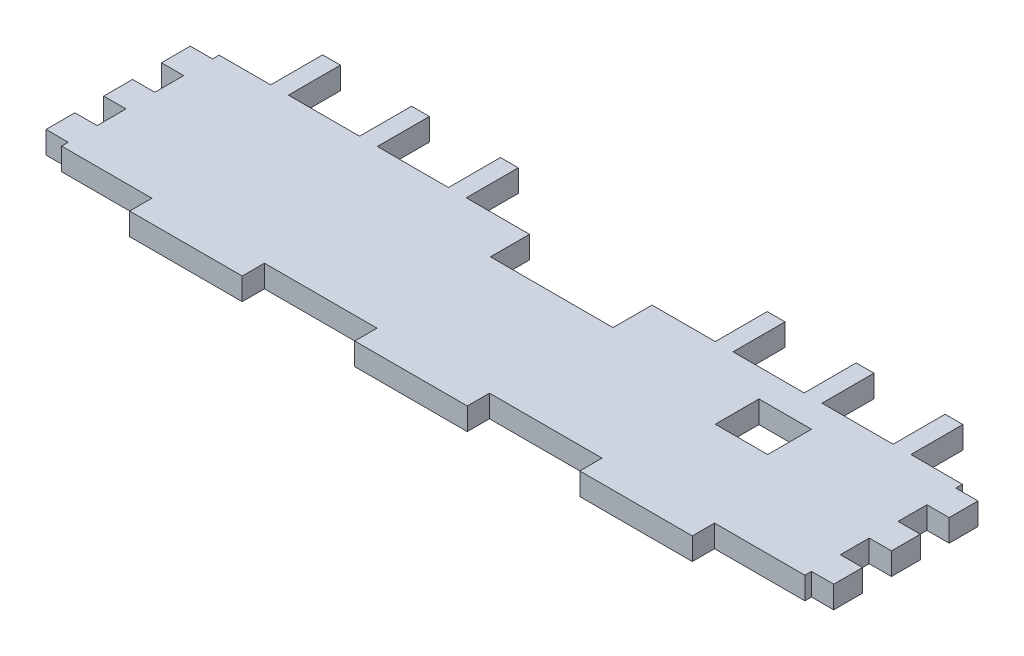
SolidWorks part; units mm, degrees
ref_plane "Front Plane" through (0, 0, 0) normal (0, 0, 1) x (1, 0, 0)
ref_plane "Top Plane" through (0, 0, 0) normal (0, 1, 0) x (1, 0, 0)
ref_plane "Right Plane" through (0, 0, 0) normal (1, 0, 0) x (0, 0, -1)
sketch "Sketch1" plane through (0, 0, 0) normal (0, 1, 0) x (1, 0, 0)
  line L48 (32.1429, 0) -> (32.1429, 6.35)
  line L49 (0, 0) -> (32.1429, 0)
  line L50 (0, 0) -> (0, 6.35)
  line L51 (0, 6.35) -> (32.1429, 6.35)
  line L52 (32.1429, 0) -> (32.1429, 6.35)
  line L53 (0, 0) -> (6.35, 0)
  line L54 (0, 0) -> (0, 8.2429)
  line L55 (0, 8.2429) -> (6.35, 8.2429)
  line L56 (6.35, 0) -> (6.35, 8.2429)
  line L57 (32.1429, 0) -> (64.2857, 0)
  line L58 (64.2857, 0) -> (64.2857, 6.35)
  line L59 (32.1429, 6.35) -> (64.2857, 6.35)
  line L60 (64.2857, 0) -> (64.2857, 6.35)
  line L61 (64.2857, 0) -> (96.4286, 0)
  line L62 (96.4286, 0) -> (96.4286, 6.35)
  line L63 (64.2857, 6.35) -> (96.4286, 6.35)
  line L64 (96.4286, 0) -> (96.4286, 6.35)
  line L65 (96.4286, 0) -> (128.5714, 0)
  line L66 (128.5714, 0) -> (128.5714, 6.35)
  line L67 (96.4286, 6.35) -> (128.5714, 6.35)
  line L72 (128.5714, 0) -> (128.5714, 6.35)
  line L73 (128.5714, 0) -> (160.7143, 0)
  line L74 (160.7143, 0) -> (160.7143, 6.35)
  line L75 (128.5714, 6.35) -> (160.7143, 6.35)
  line L76 (160.7143, 0) -> (160.7143, 6.35)
  line L77 (160.7143, 0) -> (192.8571, 0)
  line L78 (192.8571, 0) -> (192.8571, 6.35)
  line L79 (160.7143, 6.35) -> (192.8571, 6.35)
  line L80 (192.8571, 0) -> (192.8571, 6.35)
  line L81 (192.8571, 0) -> (225, 0)
  line L82 (225, 0) -> (225, 6.35)
  line L83 (192.8571, 6.35) -> (225, 6.35)
  line L84 (0, 8.2429) -> (0, 16.4857)
  line L85 (0, 8.2429) -> (6.35, 8.2429)
  line L86 (6.35, 8.2429) -> (6.35, 16.4857)
  line L87 (0, 16.4857) -> (6.35, 16.4857)
  line L88 (0, 16.4857) -> (0, 24.7286)
  line L89 (0, 16.4857) -> (6.35, 16.4857)
  line L90 (6.35, 16.4857) -> (6.35, 24.7286)
  line L91 (0, 24.7286) -> (6.35, 24.7286)
  line L98 (0, 24.7286) -> (0, 32.9714)
  line L99 (0, 24.7286) -> (6.35, 24.7286)
  line L100 (6.35, 24.7286) -> (6.35, 32.9714)
  line L101 (0, 32.9714) -> (6.35, 32.9714)
  line L102 (0, 32.9714) -> (0, 41.2143)
  line L103 (0, 32.9714) -> (6.35, 32.9714)
  line L104 (6.35, 32.9714) -> (6.35, 41.2143)
  line L105 (0, 41.2143) -> (6.35, 41.2143)
  line L106 (0, 41.2143) -> (0, 49.4571)
  line L107 (0, 41.2143) -> (6.35, 41.2143)
  line L108 (6.35, 41.2143) -> (6.35, 49.4571)
  line L109 (0, 49.4571) -> (6.35, 49.4571)
  line L110 (0, 49.4571) -> (0, 57.7)
  line L111 (0, 49.4571) -> (6.35, 49.4571)
  line L112 (6.35, 49.4571) -> (6.35, 57.7)
  line L113 (0, 57.7) -> (6.35, 57.7)
  line L114 (112.5, 0) -> (112.5, 671.069) construction
  line L115 (-187.856, 28.85) -> (254.8092, 28.85) construction
  line L116 (225, 8.2429) -> (218.65, 8.2429)
  line L117 (218.65, 0) -> (218.65, 8.2429)
  line L118 (225, 0) -> (218.65, 0)
  line L119 (225, 0) -> (225, 8.2429)
  line L120 (225, 49.4571) -> (218.65, 49.4571)
  line L121 (218.65, 49.4571) -> (218.65, 57.7)
  line L122 (225, 57.7) -> (218.65, 57.7)
  line L123 (225, 49.4571) -> (225, 57.7)
  line L124 (225, 41.2143) -> (218.65, 41.2143)
  line L125 (218.65, 41.2143) -> (218.65, 49.4571)
  line L126 (225, 49.4571) -> (218.65, 49.4571)
  line L127 (225, 41.2143) -> (225, 49.4571)
  line L128 (225, 8.2429) -> (218.65, 8.2429)
  line L129 (218.65, 8.2429) -> (218.65, 16.4857)
  line L130 (225, 16.4857) -> (218.65, 16.4857)
  line L131 (225, 8.2429) -> (225, 16.4857)
  line L132 (225, 32.9714) -> (218.65, 32.9714)
  line L133 (218.65, 32.9714) -> (218.65, 41.2143)
  line L134 (225, 41.2143) -> (218.65, 41.2143)
  line L135 (225, 32.9714) -> (225, 41.2143)
  line L136 (225, 24.7286) -> (218.65, 24.7286)
  line L137 (218.65, 24.7286) -> (218.65, 32.9714)
  line L138 (225, 32.9714) -> (218.65, 32.9714)
  line L139 (225, 24.7286) -> (225, 32.9714)
  line L140 (225, 16.4857) -> (218.65, 16.4857)
  line L141 (218.65, 16.4857) -> (218.65, 24.7286)
  line L142 (225, 24.7286) -> (218.65, 24.7286)
  line L143 (225, 16.4857) -> (225, 24.7286)
  line L144 (192.8571, 57.7) -> (225, 57.7)
  line L145 (225, 57.7) -> (225, 51.35)
  line L146 (192.8571, 51.35) -> (225, 51.35)
  line L147 (192.8571, 57.7) -> (192.8571, 51.35)
  line L148 (160.7143, 57.7) -> (192.8571, 57.7)
  line L149 (192.8571, 57.7) -> (192.8571, 51.35)
  line L150 (160.7143, 51.35) -> (192.8571, 51.35)
  line L151 (160.7143, 57.7) -> (160.7143, 51.35)
  line L152 (128.5714, 57.7) -> (160.7143, 57.7)
  line L153 (160.7143, 57.7) -> (160.7143, 51.35)
  line L154 (128.5714, 51.35) -> (160.7143, 51.35)
  line L155 (128.5714, 57.7) -> (128.5714, 51.35)
  line L156 (96.4286, 57.7) -> (128.5714, 57.7)
  line L157 (128.5714, 57.7) -> (128.5714, 51.35)
  line L158 (96.4286, 51.35) -> (128.5714, 51.35)
  line L159 (96.4286, 57.7) -> (96.4286, 51.35)
  line L160 (64.2857, 57.7) -> (96.4286, 57.7)
  line L161 (96.4286, 57.7) -> (96.4286, 51.35)
  line L162 (64.2857, 51.35) -> (96.4286, 51.35)
  line L163 (64.2857, 57.7) -> (64.2857, 51.35)
  line L164 (32.1429, 57.7) -> (64.2857, 57.7)
  line L165 (64.2857, 57.7) -> (64.2857, 51.35)
  line L166 (32.1429, 51.35) -> (64.2857, 51.35)
  line L167 (32.1429, 57.7) -> (32.1429, 51.35)
  line L168 (0, 51.35) -> (32.1429, 51.35)
  line L169 (32.1429, 57.7) -> (32.1429, 51.35)
  line L170 (0, 57.7) -> (32.1429, 57.7)
  line L171 (0, 57.7) -> (0, 51.35)
  point P56 (112.5, 6.35)
  point P58 (6.35, 28.85)
  dimension "D3" = 6.35
  dimension "D4" = 225
  dimension "D5" = 57.7
  dimension "D2" = 7
  dimension "D1" = 7
extrude "Boss-Extrude1" add sketch "Sketch1" along normal blind 6.35 contours L168 L112 L108 L104 L100 L90 L86 L56 L51 L59 L63 L67 L75 L79 L83 L117 L129 L141 L137 L133 L125 L121 L146 L150 L154 L158 L162 L166 | L156 L159 L158 L155 | L67 L62 L65 L66 | L79 L74 L77 L78 | L148 L151 L150 L147 | L164 L167 L166 L163 | L59 L48 L57 L58 | L87 L84 L55 L86 | L101 L98 L91 L100 | L109 L106 L105 L108 | L116 L131 L130 L129 | L136 L139 L132 L137 | L124 L127 L120 L125
sketch "Sketch2" plane through (0, 6.35, 0) normal (0, 1, 0) x (1, 0, 0)
  line L0 (32.1429, 57.7) -> (64.2857, 57.7) construction
  line L1 (6.35, 51.35) -> (218.65, 51.35)
  line L2 (6.35, 51.35) -> (6.35, 57.7)
  line L3 (6.35, 57.7) -> (218.65, 57.7)
  line L4 (218.65, 51.35) -> (218.65, 57.7)
  line L5 (46.46, 66.2) -> (46.46, 57.7)
  line L6 (21.06, 66.2) -> (26.14, 66.2)
  line L7 (21.06, 66.2) -> (21.06, 57.7)
  line L8 (21.06, 57.7) -> (26.14, 57.7)
  line L9 (26.14, 66.2) -> (26.14, 57.7)
  line L10 (46.46, 66.2) -> (51.54, 66.2)
  line L11 (51.54, 66.2) -> (51.54, 57.7)
  line L12 (46.46, 57.7) -> (51.54, 57.7)
  line L13 (71.86, 66.2) -> (71.86, 57.7)
  line L14 (71.86, 66.2) -> (76.94, 66.2)
  line L15 (76.94, 66.2) -> (76.94, 57.7)
  line L16 (71.86, 57.7) -> (76.94, 57.7)
  line L17 (97.26, 66.2) -> (97.26, 57.7)
  line L18 (97.26, 66.2) -> (102.34, 66.2)
  line L19 (102.34, 66.2) -> (102.34, 57.7)
  line L20 (97.26, 57.7) -> (102.34, 57.7)
  line L21 (122.66, 66.2) -> (122.66, 57.7)
  line L22 (122.66, 66.2) -> (127.74, 66.2)
  line L23 (127.74, 66.2) -> (127.74, 57.7)
  line L24 (122.66, 57.7) -> (127.74, 57.7)
  line L25 (148.06, 66.2) -> (148.06, 57.7)
  line L26 (148.06, 66.2) -> (153.14, 66.2)
  line L27 (153.14, 66.2) -> (153.14, 57.7)
  line L28 (148.06, 57.7) -> (153.14, 57.7)
  line L29 (173.46, 66.2) -> (173.46, 57.7)
  line L30 (173.46, 66.2) -> (178.54, 66.2)
  line L31 (178.54, 66.2) -> (178.54, 57.7)
  line L32 (173.46, 57.7) -> (178.54, 57.7)
  line L33 (198.86, 66.2) -> (198.86, 57.7)
  line L34 (198.86, 66.2) -> (203.94, 66.2)
  line L35 (203.94, 66.2) -> (203.94, 57.7)
  line L36 (198.86, 57.7) -> (203.94, 57.7)
  line L45 (224.26, 66.2) -> (224.26, 57.7) [skipped]
  line L46 (224.26, 66.2) -> (229.34, 66.2) [skipped]
  line L47 (229.34, 66.2) -> (229.34, 57.7) [skipped]
  line L48 (224.26, 57.7) -> (229.34, 57.7) [skipped]
  line L49 (249.66, 66.2) -> (249.66, 57.7) [skipped]
  line L50 (249.66, 66.2) -> (254.74, 66.2) [skipped]
  line L51 (254.74, 66.2) -> (254.74, 57.7) [skipped]
  line L52 (249.66, 57.7) -> (254.74, 57.7) [skipped]
  line L53 (112.5, 0) -> (112.5, 77.7946) construction
  line L55 (96.4286, 0) -> (128.5714, 0) construction
  line L56 (112.5, 66.2) -> (122.66, 66.2) construction
  line L57 (112.5, 66.2) -> (102.34, 66.2) construction
  point P44 (112.5, 0)
  point P46 (49, 66.2)
  point P47 (23.6, 66.2)
  dimension "D2" = 5.08
  dimension "D3" = 25.4
  dimension "D4" = 8.5
  dimension "D1" = 10
extrude "Boss-Extrude2" add sketch "Sketch2" against normal up to surface (6.35 mm away) contours L1 L4 L3 L2 | L9 L6 L7 L3 | L11 L10 L5 L3 | L15 L14 L13 L3 | L19 L18 L17 L3 | L35 L34 L33 L3 | L31 L30 L29 L3 | L21 L24 L23 L22 | L27 L28 L25 L26 up to face at (112.5, 0, -28.85)
sketch "Sketch3" plane through (0, 6.35, 0) normal (0, 1, 0) x (1, 0, 0)
  line L1 (112.5, 0) -> (112.5, 57.7) construction
  line L2 (95, 40.2) -> (130, 40.2)
  line L3 (95, 40.2) -> (95, 66.2)
  line L4 (95, 66.2) -> (130, 66.2)
  line L5 (130, 40.2) -> (130, 66.2)
  line L6 (96.4286, 0) -> (128.5714, 0) construction
  line L7 (102.34, 57.7) -> (122.66, 57.7) construction
  line L8 (127.74, 57.7) -> (148.06, 57.7) construction
  line L9 (122.66, 66.2) -> (127.74, 66.2) construction
  point P10 (112.5, 66.2)
  dimension "D1" = 35
  dimension "D2" = 17.5
extrude "Cut-Extrude1" cut sketch "Sketch3" against normal through all
sketch "Sketch4" plane through (0, 6.35, 0) normal (0, 1, 0) x (1, 0, 0)
  line L0 (203.94, 66.2) -> (203.94, 57.7) construction
  line L1 (6.35, 57.7) -> (21.06, 57.7)
  line L2 (6.35, 57.7) -> (6.35, 51.35)
  line L3 (6.35, 51.35) -> (21.06, 51.35)
  line L4 (21.06, 57.7) -> (21.06, 51.35)
  line L5 (26.14, 57.7) -> (46.46, 57.7)
  line L6 (26.14, 57.7) -> (26.14, 51.35)
  line L7 (26.14, 51.35) -> (46.46, 51.35)
  line L8 (46.46, 57.7) -> (46.46, 51.35)
  line L9 (218.65, 57.7) -> (203.94, 57.7)
  line L10 (218.65, 57.7) -> (218.65, 51.35)
  line L11 (218.65, 51.35) -> (203.94, 51.35)
  line L12 (203.94, 57.7) -> (203.94, 51.35)
  line L13 (198.86, 57.7) -> (178.54, 57.7)
  line L14 (198.86, 57.7) -> (198.86, 51.35)
  line L15 (198.86, 51.35) -> (178.54, 51.35)
  line L16 (178.54, 57.7) -> (178.54, 51.35)
  line L17 (203.94, 57.7) -> (218.65, 57.7) construction
  dimension "D1" = 6.35
extrude "Cut-Extrude2" cut sketch "Sketch4" against normal up to surface (6.35 mm away) up to face at (112.5, 0, -37.3706)
sketch "Sketch5" plane through (0, 6.35, 0) normal (0, 1, 0) x (1, 0, 0)
  line L1 (51.54, 57.7) -> (71.86, 57.7)
  line L2 (51.54, 57.7) -> (51.54, 51.35)
  line L3 (51.54, 51.35) -> (71.86, 51.35)
  line L4 (71.86, 57.7) -> (71.86, 51.35)
  line L5 (76.94, 57.7) -> (95, 57.7)
  line L6 (76.94, 57.7) -> (76.94, 51.35)
  line L7 (76.94, 51.35) -> (95, 51.35)
  line L8 (95, 57.7) -> (95, 51.35)
  line L9 (153.14, 66.2) -> (153.14, 57.7) construction
  line L10 (130, 57.7) -> (148.06, 57.7)
  line L11 (130, 57.7) -> (130, 51.35)
  line L12 (130, 51.35) -> (148.06, 51.35)
  line L13 (148.06, 57.7) -> (148.06, 51.35)
  line L14 (153.14, 57.7) -> (173.46, 57.7)
  line L15 (153.14, 57.7) -> (153.14, 51.35)
  line L16 (153.14, 51.35) -> (173.46, 51.35)
  line L17 (173.46, 57.7) -> (173.46, 51.35)
  line L18 (148.06, 66.2) -> (148.06, 57.7) construction
  line L19 (71.86, 66.2) -> (71.86, 57.7) construction
  line L20 (26.14, 51.35) -> (46.46, 51.35) construction
  line L21 (173.46, 66.2) -> (173.46, 57.7) construction
extrude "Cut-Extrude3" cut sketch "Sketch5" against normal through all
sketch "Sketch8" plane through (0, 6.35, 0) normal (0, 1, 0) x (1, 0, 0)
  line L0 (173.46, 66.2) -> (178.54, 66.2) construction
  line L1 (168.5, 43.4) -> (183.5, 43.4)
  line L2 (168.5, 43.4) -> (168.5, 30.9)
  line L3 (168.5, 30.9) -> (183.5, 30.9)
  line L4 (183.5, 43.4) -> (183.5, 30.9)
  point P4 (183.5, 37.15)
  point P6 (176, 43.4)
  point P9 (176, 66.2)
  dimension "D1" = 15
  dimension "D2" = 12.5
  dimension "D3" = 14.2
extrude "Cut-Extrude6" cut sketch "Sketch8" against normal through all
